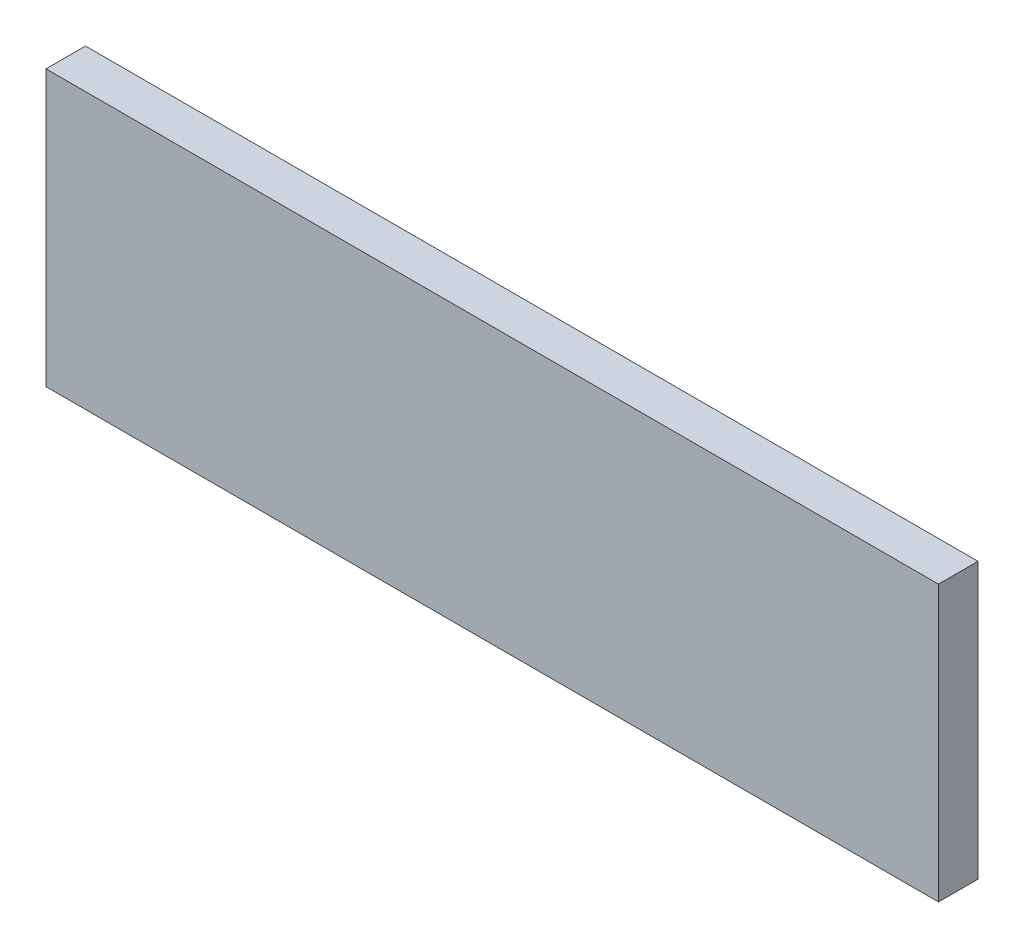
SolidWorks part; units mm, degrees
ref_plane "Front Plane" through (0, 0, 0) normal (0, 0, 1) x (1, 0, 0)
ref_plane "Top Plane" through (0, 0, 0) normal (0, 1, 0) x (1, 0, 0)
ref_plane "Right Plane" through (0, 0, 0) normal (1, 0, 0) x (0, 0, -1)
sketch "Sketch1" plane through (0, 0, 0) normal (0, 0, 1) x (1, 0, 0)
  line L1 (-137.8, 42.5) -> (137.8, 42.5)
  line L2 (-137.8, 42.5) -> (-137.8, -42.5)
  line L3 (-137.8, -42.5) -> (137.8, -42.5)
  line L4 (137.8, 42.5) -> (137.8, -42.5)
  line L5 (-137.8, 42.5) -> (137.8, -42.5) construction
  line L6 (-137.8, -42.5) -> (137.8, 42.5) construction
  point P0 (0, 0)
  dimension "D1" = 275.6
  dimension "D2" = 85
extrude "Boss-Extrude1" add sketch "Sketch1" along normal blind 12.2
